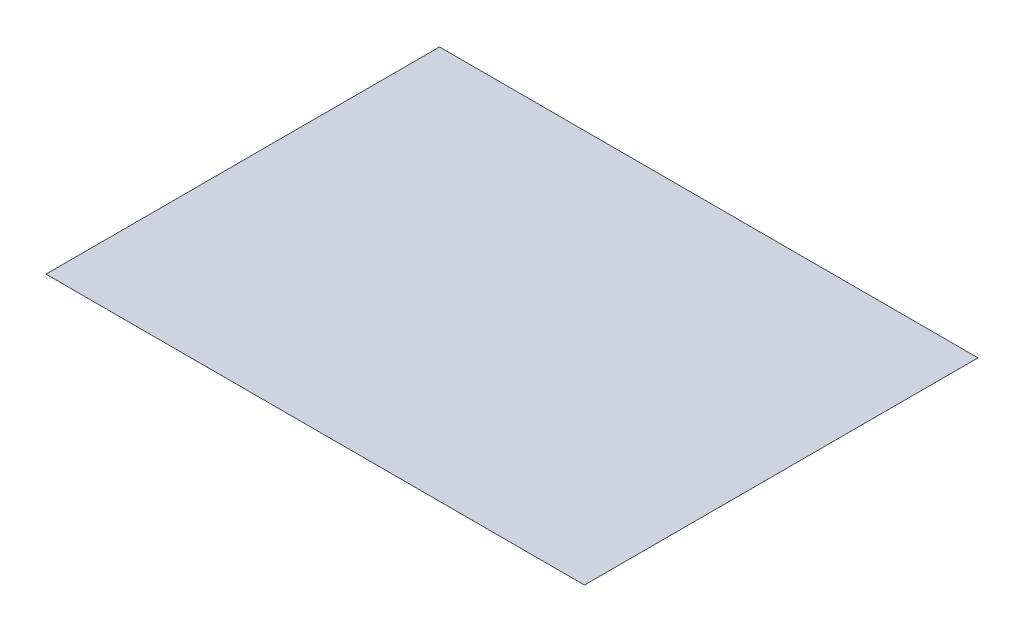
SolidWorks part; units mm, degrees
ref_plane "Front Plane" through (0, 0, 0) normal (0, 0, 1) x (1, 0, 0)
ref_plane "Top Plane" through (0, 0, 0) normal (0, 1, 0) x (1, 0, 0)
ref_plane "Right Plane" through (0, 0, 0) normal (1, 0, 0) x (0, 0, -1)
sketch "Sketch1" plane through (0, 0, 0) normal (0, 1, 0) x (1, 0, 0)
  line L1 (65, -47.5) -> (-65, -47.5)
  line L2 (65, -47.5) -> (65, 47.5)
  line L3 (65, 47.5) -> (-65, 47.5)
  line L4 (-65, -47.5) -> (-65, 47.5)
  line L5 (65, -47.5) -> (-65, 47.5) construction
  line L6 (65, 47.5) -> (-65, -47.5) construction
  point P0 (0, 0)
  dimension "D1" = 130
  dimension "D2" = 95
extrude "Boss-Extrude1" add sketch "Sketch1" along normal blind 0.005
